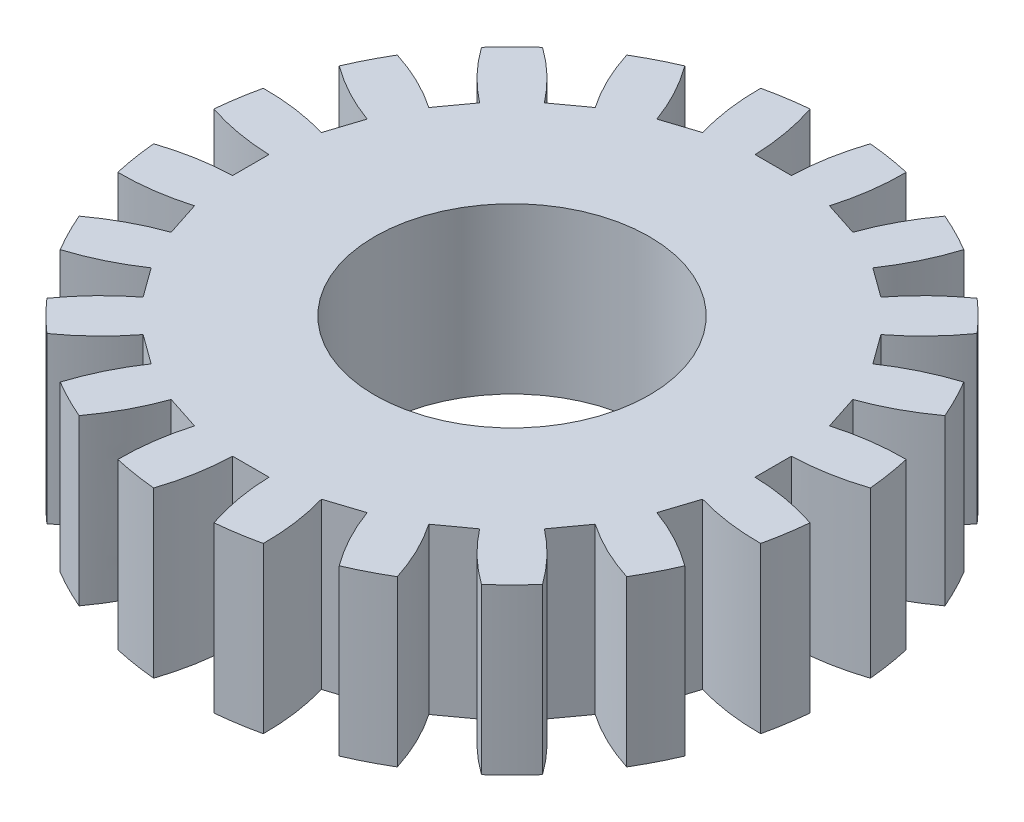
SolidWorks part; units mm, degrees
ref_plane "前视基准面" through (0, 0, 0) normal (0, 0, 1) x (1, 0, 0)
ref_plane "上视基准面" through (0, 0, 0) normal (0, 1, 0) x (1, 0, 0)
ref_plane "右视基准面" through (0, 0, 0) normal (1, 0, 0) x (0, 0, -1)
other "Configuration Table"
sketch "草图1" plane through (0, 0, 0) normal (0, 1, 0) x (1, 0, 0)
  circle A0 centre (0, 0) radius 60
  circle A1 centre (0, 0) radius 25
  dimension "D1" = 50
  dimension "D2" = 120
extrude "凸台-拉伸1" add sketch "草图1" along normal blind 30
sketch "草图4" plane through (0, 30, 0) normal (0, 1, 0) x (1, 0, 0)
  line L0 (0, 60) -> (0, -68.89) construction
  line L1 (-3.308, 47.5531) -> (3.308, 47.5531)
  circle A0 centre (0, 0) radius 60 construction
  spline S0 degree 2 poles (5.4846, 59.7488) (3.5071, 53.8001) (3.308, 47.5531) knots 0 0 0 1 1 1
  spline S1 degree 2 poles (-5.4846, 59.7488) (-3.5071, 53.8001) (-3.308, 47.5531) knots 0 0 0 1 1 1
extrude "切除-拉伸2" cut sketch "草图4" against normal blind 30 and the other way through all
sketch "草图5" plane through (0, 0, 0) normal (0, 0, 1) x (1, 0, 0)
  line L0 (0, 55.7077) -> (0, -20.4675) construction
pattern_circular "阵列(圆周)2" count 20 over 360 about axis through (0, 55.7077, 0) along (0, -1, 0) of "切除-拉伸2"
